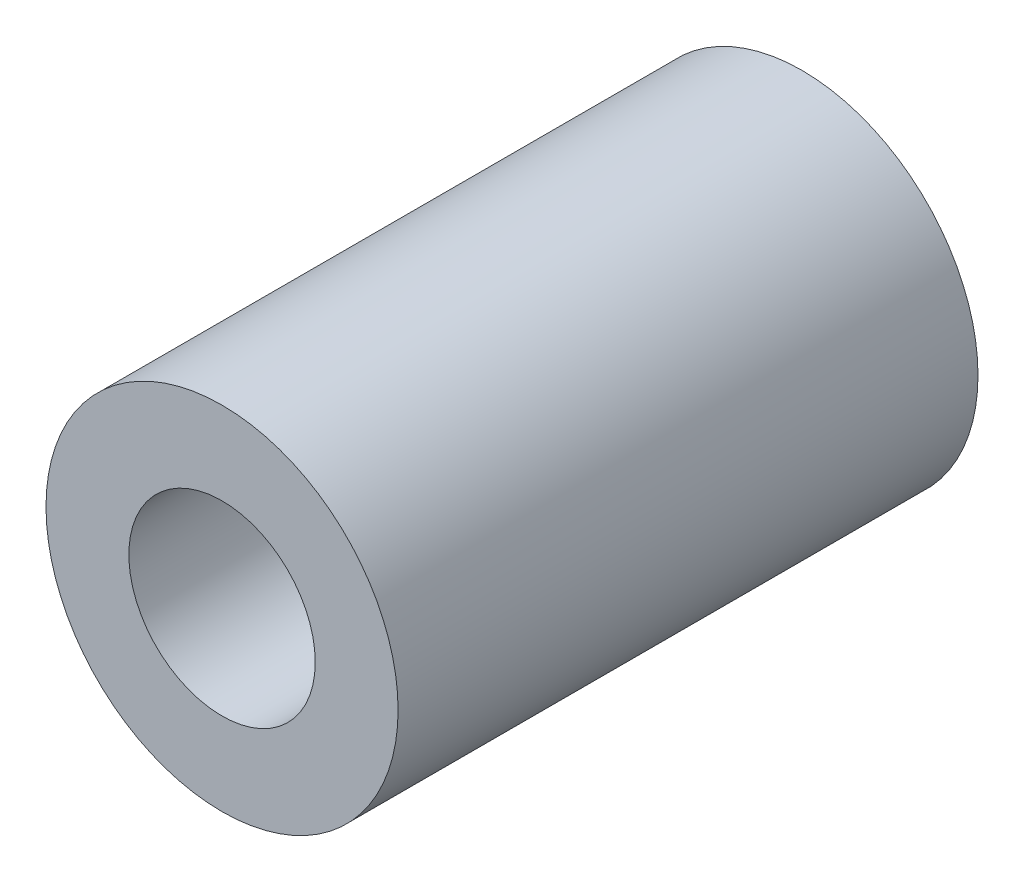
SolidWorks part; units mm, degrees
ref_plane "Plan de face" through (0, 0, 0) normal (0, 0, 1) x (1, 0, 0)
ref_plane "Plan de dessus" through (0, 0, 0) normal (0, 1, 0) x (1, 0, 0)
ref_plane "Plan de droite" through (0, 0, 0) normal (1, 0, 0) x (0, 0, -1)
sketch "Esquisse1" plane through (0, 0, 0) normal (0, 0, 1) x (1, 0, 0)
  circle A0 centre (0, 0) radius 4.5
  circle A1 centre (0, 0) radius 8.5
  dimension "D1" = 9
  dimension "D2" = 4
extrude "Boss.-Extru.1" add sketch "Esquisse1" along normal blind 28
